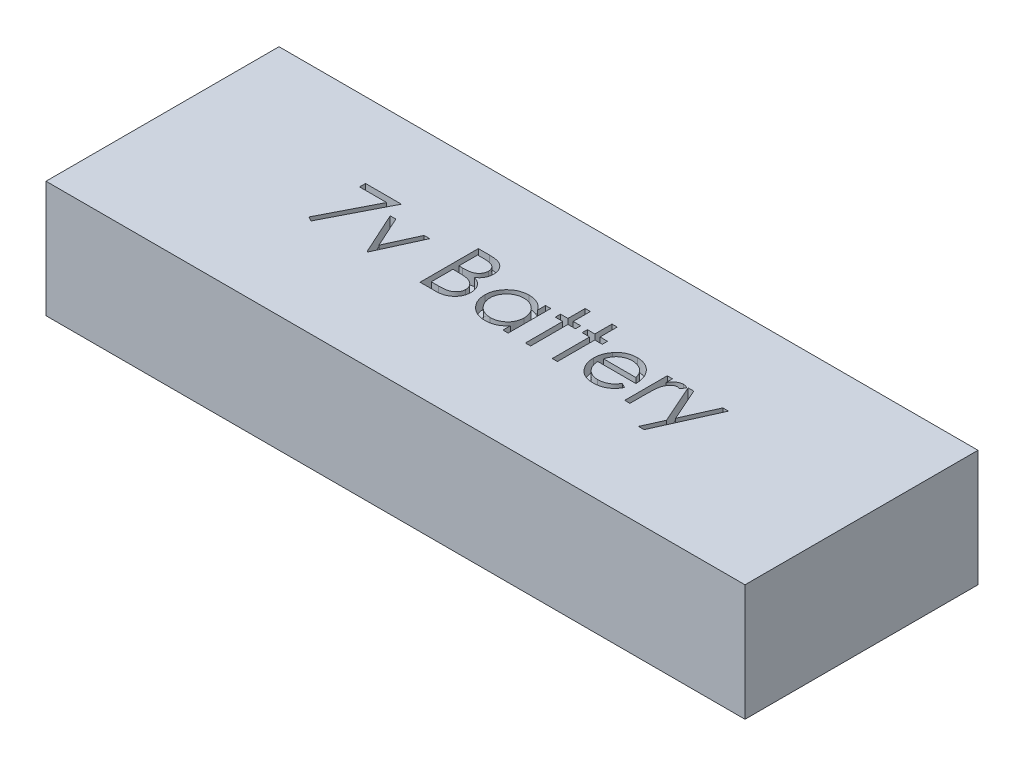
SolidWorks part; units mm, degrees
ref_plane "Front Plane" through (0, 0, 0) normal (0, 0, 1) x (1, 0, 0)
ref_plane "Top Plane" through (0, 0, 0) normal (0, 1, 0) x (1, 0, 0)
ref_plane "Right Plane" through (0, 0, 0) normal (1, 0, 0) x (0, 0, -1)
sketch "Sketch1" plane through (0, 0, 0) normal (0, 1, 0) x (1, 0, 0)
  line L1 (-76.2, -25.4) -> (76.2, -25.4)
  line L2 (-76.2, -25.4) -> (-76.2, 25.4)
  line L3 (-76.2, 25.4) -> (76.2, 25.4)
  line L4 (76.2, -25.4) -> (76.2, 25.4)
  line L5 (-76.2, -25.4) -> (76.2, 25.4) construction
  line L6 (-76.2, 25.4) -> (76.2, -25.4) construction
  point P0 (0, 0)
  dimension "D1" = 152.4
  dimension "D2" = 50.8
extrude "Boss-Extrude1" add sketch "Sketch1" along normal blind 25.4
sketch "Sketch2" plane through (0, 25.4, 0) normal (0, 1, 0) x (1, 0, 0)
  text T0 "7v Battery" font "Century Gothic" height in points 48
extrude "Cut-Extrude1" cut sketch "Sketch2" against normal blind 2.54
